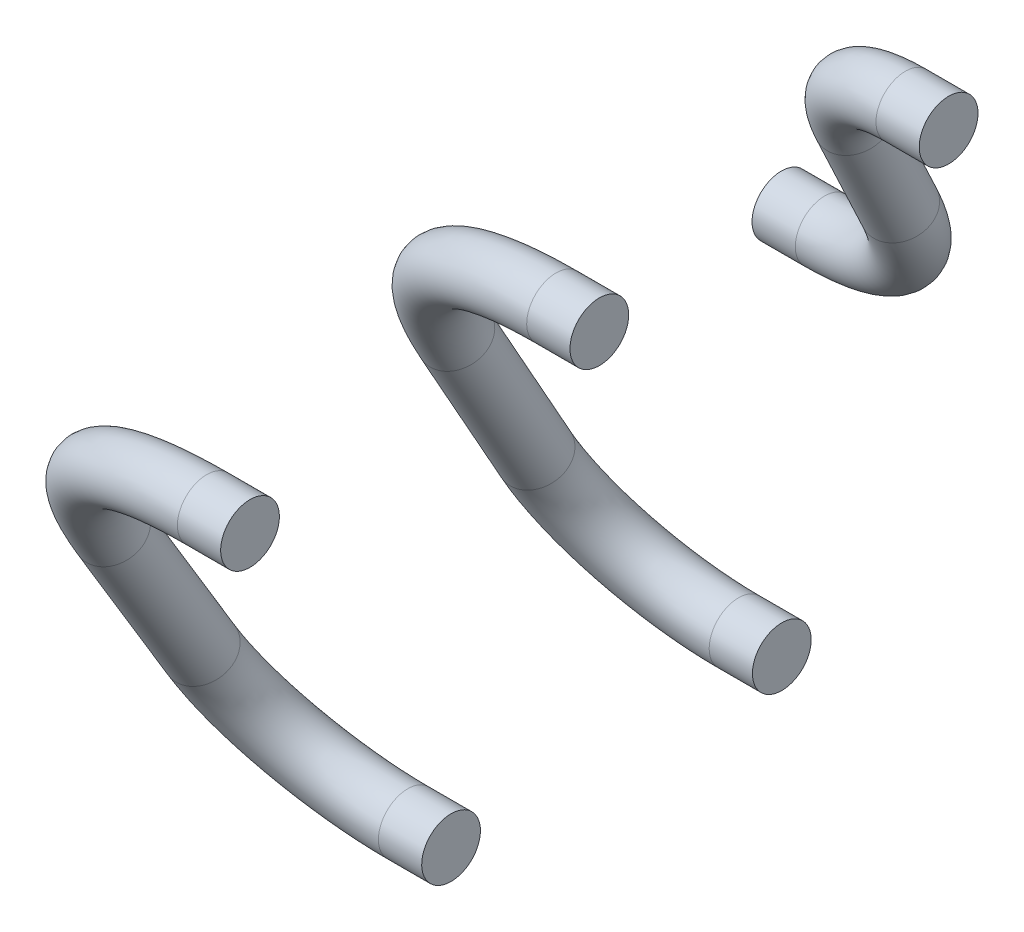
SolidWorks part; units mm, degrees
ref_plane "Front Plane" through (0, 0, 0) normal (0, 0, 1) x (1, 0, 0)
ref_plane "Top Plane" through (0, 0, 0) normal (0, 1, 0) x (1, 0, 0)
ref_plane "Right Plane" through (0, 0, 0) normal (1, 0, 0) x (0, 0, -1)
ref_plane "平面3" through (0, 24.3702, -49.2589) normal (0, 0.4434, -0.8963) x (-1, 0, 0)
sketch "ｽｹｯﾁ6" plane through (0, 24.3702, -49.2589) normal (0, 0.4434, -0.8963) x (-1, 0, 0)
  line L0 (125.95, 11.8595) -> (132.95, 11.8595)
  line L1 (125.95, 19.3595) -> (125.95, 4.3595) construction
  line L2 (169.5, -41.1357) -> (176.5, -41.1357)
  line L3 (147.5763, -2.1497) -> (148.3852, -20.9116)
  arc A0 (132.95, 11.8595) -> (147.5763, -2.1497) centre (132.95, -2.7803) cw
  arc A1 (169.5, -41.1357) -> (148.3852, -20.9116) centre (169.5, -20.0013) cw
  dimension "D1" = 7
ref_plane "平面4" through (-176.5, 0, 0) normal (1, 0, 0) x (0, 0, -1)
sketch "ｽｹｯﾁ7" plane through (-176.5, 0, 0) normal (1, 0, 0) x (0, 0, -1)
  circle A0 centre (67.5, -12.5) radius 4.75
  dimension "D1" = 9.5
sweep "ｽｲｰﾌﾟ1" add profiles "ｽｹｯﾁ7" path "ｽｹｯﾁ6"
ref_plane "平面5" through (0, 3.0395, -5.4207) normal (0, -0.4891, 0.8722) x (1, 0, 0)
sketch "ｽｹｯﾁ8" plane through (0, 3.0395, -5.4207) normal (0, -0.4891, 0.8722) x (1, 0, 0)
  line L0 (-125.95, 36.6419) -> (-132.95, 36.6419)
  line L1 (-125.95, 29.1419) -> (-125.95, 44.1419) construction
  line L2 (-164.6838, 4.908) -> (-164.6838, -21.6112)
  line L3 (-142.6838, -43.6112) -> (-135.6838, -43.6112)
  line L4 (-131.95, 44.1419) -> (-131.95, 29.1419) construction
  line L5 (-141.6838, -36.1112) -> (-141.6838, -51.1112) construction
  arc A0 (-132.95, 36.6419) -> (-164.6838, 4.908) centre (-132.95, 4.908) ccw
  arc A1 (-164.6838, -21.6112) -> (-142.6838, -43.6112) centre (-142.6838, -21.6112) ccw
  point P9 (-135.6838, -43.6112)
  point P11 (-144.0007, -43.6112)
  point P15 (-168.6663, -17.6287)
  dimension "D1" = 1
  dimension "D2" = 23
ref_plane "平面6" through (-125.95, 0, 0) normal (1, 0, 0) x (0, 0, -1)
sketch "ｽｹｯﾁ9" plane through (-125.95, 0, 0) normal (1, 0, 0) x (0, 0, -1)
  circle A0 centre (-12.5, 35) radius 4.75
  dimension "D1" = 9.5
sweep "ｽｲｰﾌﾟ2" add profiles "ｽｹｯﾁ9" path "ｽｹｯﾁ8"
ref_plane "平面7" through (0, -21.1801, 35.0913) normal (0, -0.5167, 0.8561) x (1, 0, 0)
sketch "ｽｹｯﾁ10" plane through (0, -21.1801, 35.0913) normal (0, -0.5167, 0.8561) x (1, 0, 0)
  line L0 (-125.95, 65.6202) -> (-132.95, 65.6202)
  line L1 (-125.95, 58.1202) -> (-125.95, 73.1202) construction
  line L2 (-135.6838, -16.1421) -> (-142.6838, -16.1421)
  line L3 (-135.6838, -23.6421) -> (-135.6838, -8.6421) construction
  line L4 (-164.6838, 5.8579) -> (-164.6838, 33.8863)
  line L7 (-141.6838, -8.6421) -> (-141.6838, -23.6421) construction
  arc A0 (-142.6838, -16.1421) -> (-164.6838, 5.8579) centre (-142.6838, 5.8579) cw
  arc A1 (-164.6838, 33.8863) -> (-132.95, 65.6202) centre (-132.95, 33.8863) cw
  point P13 (-192.0686, 46.1265)
  point P14 (-150.529, 66.6792)
  point P16 (-146.1869, -16.2855)
  point P17 (0, 0)
  point P18 (-171.2824, 12.4565)
  point P19 (-156.2238, 42.3463)
  point P21 (-164.589, 5.7631)
  point P22 (-134.011, 65.6202)
  dimension "D1" = 1
  dimension "D2" = 23
ref_plane "平面8" through (-125.95, 0, 0) normal (1, 0, 0) x (0, 0, -1)
sketch "ｽｹｯﾁ11" plane through (-125.95, 0, 0) normal (1, 0, 0) x (0, 0, -1)
  circle A0 centre (-69, 35) radius 4.75
  dimension "D1" = 9.5
sweep "ｽｲｰﾌﾟ3" add profiles "ｽｹｯﾁ11" path "ｽｹｯﾁ10"
